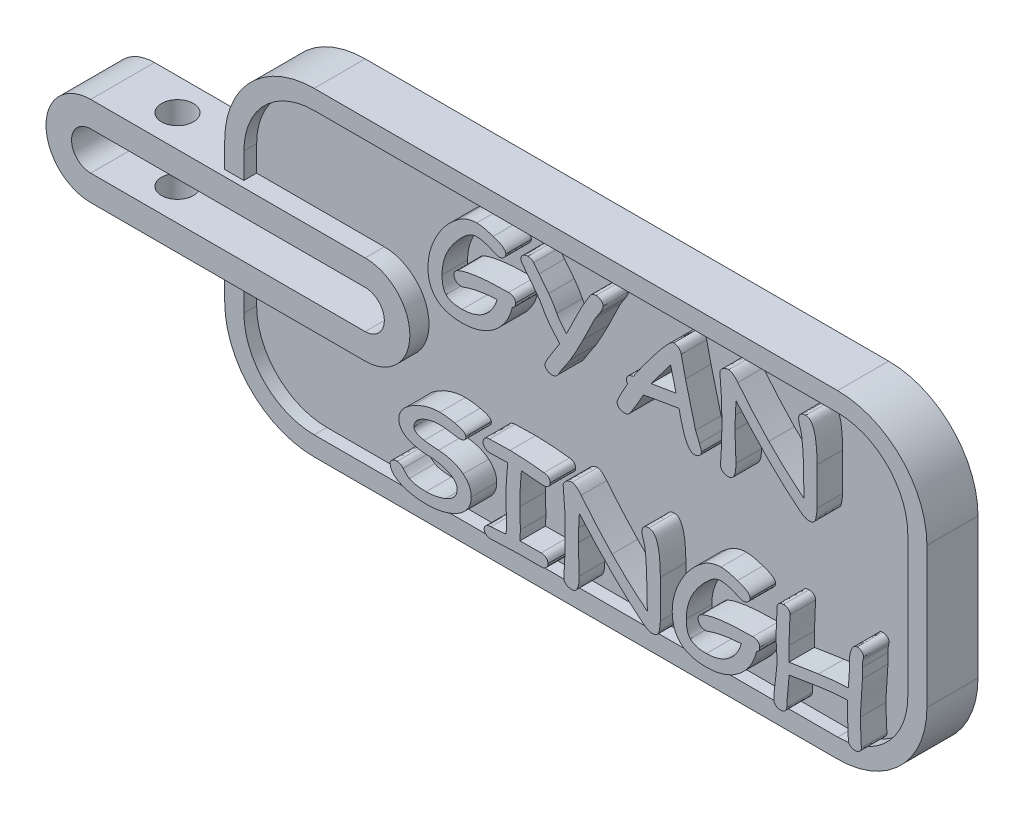
SolidWorks part; units mm, degrees
ref_plane "Front Plane" through (0, 0, 0) normal (0, 0, 1) x (1, 0, 0)
ref_plane "Top Plane" through (0, 0, 0) normal (0, 1, 0) x (1, 0, 0)
ref_plane "Right Plane" through (0, 0, 0) normal (1, 0, 0) x (0, 0, -1)
sketch "Sketch1" plane through (0, 0, 0) normal (0, 0, 1) x (1, 0, 0)
  line L1 (-20.5, -12.5) -> (20.5, -12.5)
  line L2 (-27.5, -5.5) -> (-27.5, 5.5)
  line L3 (-20.5, 12.5) -> (20.5, 12.5)
  line L4 (27.5, -5.5) -> (27.5, 5.5)
  line L5 (-27.5, -12.5) -> (27.5, 12.5) construction
  line L6 (-27.5, 12.5) -> (27.5, -12.5) construction
  arc A0 (20.5, 12.5) -> (27.5, 5.5) centre (20.5, 5.5) cw
  arc A1 (27.5, -5.5) -> (20.5, -12.5) centre (20.5, -5.5) cw
  arc A2 (-20.5, -12.5) -> (-27.5, -5.5) centre (-20.5, -5.5) cw
  arc A3 (-20.5, 12.5) -> (-27.5, 5.5) centre (-20.5, 5.5) ccw
  point P0 (0, 0)
  dimension "D3" = 7
  dimension "D1" = 25
  dimension "D2" = 55
extrude "Boss-Extrude2" add sketch "Sketch1" along normal blind 4
sketch "Sketch3" plane through (0, 0, 4) normal (0, 0, 1) x (1, 0, 0)
  line L8 (20.5, 11) -> (-20.5, 11)
  line L9 (-26, 5.5) -> (-26, -5.5)
  line L10 (-20.5, -11) -> (20.5, -11)
  line L11 (26, -5.5) -> (26, 5.5)
  line L12 (20.5, 11) -> (-20.5, 11)
  line L13 (-26, 5.5) -> (-26, -5.5)
  line L14 (-20.5, -11) -> (20.5, -11)
  line L15 (26, -5.5) -> (26, 5.5)
  arc A8 (26, 5.5) -> (20.5, 11) centre (20.5, 5.5) ccw
  arc A9 (-20.5, 11) -> (-26, 5.5) centre (-20.5, 5.5) ccw
  arc A10 (-26, -5.5) -> (-20.5, -11) centre (-20.5, -5.5) ccw
  arc A11 (20.5, -11) -> (26, -5.5) centre (20.5, -5.5) ccw
  arc A12 (26, 5.5) -> (20.5, 11) centre (20.5, 5.5) ccw
  arc A13 (-20.5, 11) -> (-26, 5.5) centre (-20.5, 5.5) ccw
  arc A14 (-26, -5.5) -> (-20.5, -11) centre (-20.5, -5.5) ccw
  arc A15 (20.5, -11) -> (26, -5.5) centre (20.5, -5.5) ccw
  dimension "D1" = 1.5
extrude "Cut-Extrude1" cut sketch "Sketch3" against normal blind 1
sketch "Sketch4" plane through (0, 0, 0) normal (0, 0, -1) x (-1, 0, 0)
  line L8 (-26, 5.5) -> (-26, -5.5)
  line L9 (-20.5, -11) -> (20.5, -11)
  line L10 (26, -5.5) -> (26, 5.5)
  line L11 (20.5, 11) -> (-20.5, 11)
  line L12 (-26, 5.5) -> (-26, -5.5)
  line L13 (-20.5, -11) -> (20.5, -11)
  line L14 (26, -5.5) -> (26, 5.5)
  line L15 (20.5, 11) -> (-20.5, 11)
  arc A8 (-20.5, 11) -> (-26, 5.5) centre (-20.5, 5.5) ccw
  arc A9 (-26, -5.5) -> (-20.5, -11) centre (-20.5, -5.5) ccw
  arc A10 (20.5, -11) -> (26, -5.5) centre (20.5, -5.5) ccw
  arc A11 (26, 5.5) -> (20.5, 11) centre (20.5, 5.5) ccw
  arc A12 (-20.5, 11) -> (-26, 5.5) centre (-20.5, 5.5) ccw
  arc A13 (-26, -5.5) -> (-20.5, -11) centre (-20.5, -5.5) ccw
  arc A14 (20.5, -11) -> (26, -5.5) centre (20.5, -5.5) ccw
  arc A15 (26, 5.5) -> (20.5, 11) centre (20.5, 5.5) ccw
  dimension "D1" = 1.5
extrude "Cut-Extrude2" cut sketch "Sketch4" against normal blind 1
sketch "Sketch5" plane through (0, 0, 3) normal (0, 0, 1) x (1, 0, 0)
  line L0 (-37.5, -1.5) -> (-27.5, -1.5)
  line L1 (-27.5, -1.5) -> (-26, -1.5)
  line L2 (-26, 5.5) -> (-26, -5.5) construction
  line L3 (-37.5, 1.5) -> (-27.5, 1.5)
  line L4 (-27.5, 5.5) -> (-27.5, -5.5) construction
  line L5 (-27.5, 1.5) -> (-26, 1.5)
  line L6 (-26, 5.5) -> (-26, -5.5) construction
  line L7 (-26, -1.5) -> (-16, -1.5)
  line L8 (-16, 3.5) -> (-26, 3.5)
  line L9 (-16, 1.5) -> (-26, 1.5)
  line L10 (-37.5, 3.5) -> (-27.5, 3.5)
  line L11 (-27.5, 3.5) -> (-26, 3.5)
  line L12 (-37.5, -3.5) -> (-27.5, -3.5)
  line L13 (-27.5, -3.5) -> (-26, -3.5)
  line L14 (-26, -3.5) -> (-16, -3.5)
  arc A0 (-37.5, -1.5) -> (-37.5, 1.5) centre (-37.5, 0) cw
  arc A1 (-16, 1.5) -> (-16, -1.5) centre (-16, 0) cw
  arc A2 (-16, 3.5) -> (-16, -3.5) centre (-16, 0) cw
  arc A3 (-37.5, -3.5) -> (-37.5, 3.5) centre (-37.5, 0) cw
  line M25 (-26, 5.5) -> (-26, -5.5)
  dimension "D3" = 10
  dimension "D1" = 10
  dimension "D2" = 10
  dimension "D4" = 2
  dimension "D5" = 2
  dimension "D6" = 2
extrude "Boss-Extrude5" add sketch "Sketch5" against normal blind 3.5 contours A3 L12 L13 L1 L0 A0 L3 L5 L11 L10 M25 | A2 L8 L9 A1 L7 L14 M25
sketch "Sketch6" plane through (0, 0, -0.5) normal (0, 0, -1) x (-1, 0, 0)
  line L0 (16, 3.5) -> (37.5, 3.5)
  line L1 (37.5, 3.5) -> (16, 3.5) construction
  line L3 (37.5, -1.5) -> (16, -1.5)
  line L5 (37.5, -3.5) -> (16, -3.5)
  line L6 (16, 1.5) -> (37.5, 1.5)
  line L7 (16, -1.5) -> (37.5, -1.5)
  arc A0 (16, 3.5) -> (16, -3.5) centre (16, 0) ccw construction
  arc A1 (37.5, -1.5) -> (37.5, 1.5) centre (37.5, 0) ccw construction
  arc A2 (16, -3.5) -> (16, 3.5) centre (16, 0) cw
  arc A3 (37.5, 3.5) -> (37.5, -3.5) centre (37.5, 0) cw
  arc A4 (37.5, -1.5) -> (37.5, 1.5) centre (37.5, 0) ccw
  arc A5 (16, 1.5) -> (16, -1.5) centre (16, 0) ccw
  line M11 (16, -3.5) -> (37.5, -3.5)
  arc M12 (37.5, -3.5) -> (37.5, 3.5) centre (37.5, 0) ccw
  line M13 (37.5, 3.5) -> (16, 3.5)
  arc M14 (16, 3.5) -> (16, -3.5) centre (16, 0) ccw
  arc M15 (16, -1.5) -> (16, 1.5) centre (16, 0) cw
  line M16 (16, 1.5) -> (37.5, 1.5)
  arc M17 (37.5, 1.5) -> (37.5, -1.5) centre (37.5, 0) cw
  line M18 (37.5, -1.5) -> (16, -1.5)
extrude "Boss-Extrude6" add sketch "Sketch6" against normal blind 5 contours M14 M11 M12 M13 M18 M15 M16 M17
sketch "Sketch7" plane through (0, 0, 3) normal (0, 0, 1) x (1, 0, 0)
  line L0 (-37.5, -1.5) -> (-16, -1.5) construction
  line L1 (-26, -1.5) -> (-16, -1.5)
  line L2 (-26, -1.5) -> (-26, 1.5)
  line L3 (-26, 1.5) -> (-16, 1.5)
  line L5 (-26, 1.5) -> (-26, -1.5) construction
  arc A0 (-16, 1.5) -> (-16, -1.5) centre (-16, 0) cw
extrude "Cut-Extrude3" cut sketch "Sketch7" against normal blind 5
sketch "Sketch8" plane through (0, 0, 4) normal (0, 0, 1) x (1, 0, 0)
  line L1 (-27.5, -1.5) -> (-26, -1.5)
  line L2 (-27.5, -1.5) -> (-27.5, 1.5)
  line L3 (-27.5, 1.5) -> (-26, 1.5)
  line L4 (-26, -1.5) -> (-26, 1.5)
extrude "Cut-Extrude4" cut sketch "Sketch8" against normal blind 5
sketch "Sketch9" plane through (0, -3.5, 0) normal (0, -1, 0) x (1, 0, 0)
  circle A0 centre (-33.2031, 2) radius 1.25
  dimension "D2" = 2.5
extrude "Cut-Extrude5" cut sketch "Sketch9" against normal blind 10
sketch "Sketch11" plane through (0, 0, 3) normal (0, 0, 1) x (1, 0, 0)
  text T0 " GYAN \r\nSINGH" font "Comic Sans MS" height in points 24
extrude "Boss-Extrude7" add sketch "Sketch11" along normal blind 2
sketch "Sketch12" plane through (0, 0, 1) normal (0, 0, -1) x (-1, 0, 0)
  line L0 (0, -0.4954) -> (0, -5.9453)
  circle A0 centre (0, 0) radius 8.4427
  circle A1 centre (-4.9341, 3.6332) radius 1.4037
  circle A2 centre (2.9104, 3.6332) radius 1.4863
  arc A3 (-3.0349, -3.5506) -> (2.9104, -3.5506) centre (-0.0623, -0.578) ccw
  arc A4 (-3.0349, -3.5506) -> (2.9104, -3.5506) centre (-0.0623, -3.5506) ccw
  circle A5 centre (0, 0) radius 9.9427
  dimension "D1" = 1.5
extrude "Boss-Extrude8" add sketch "Sketch12" along normal blind 2
